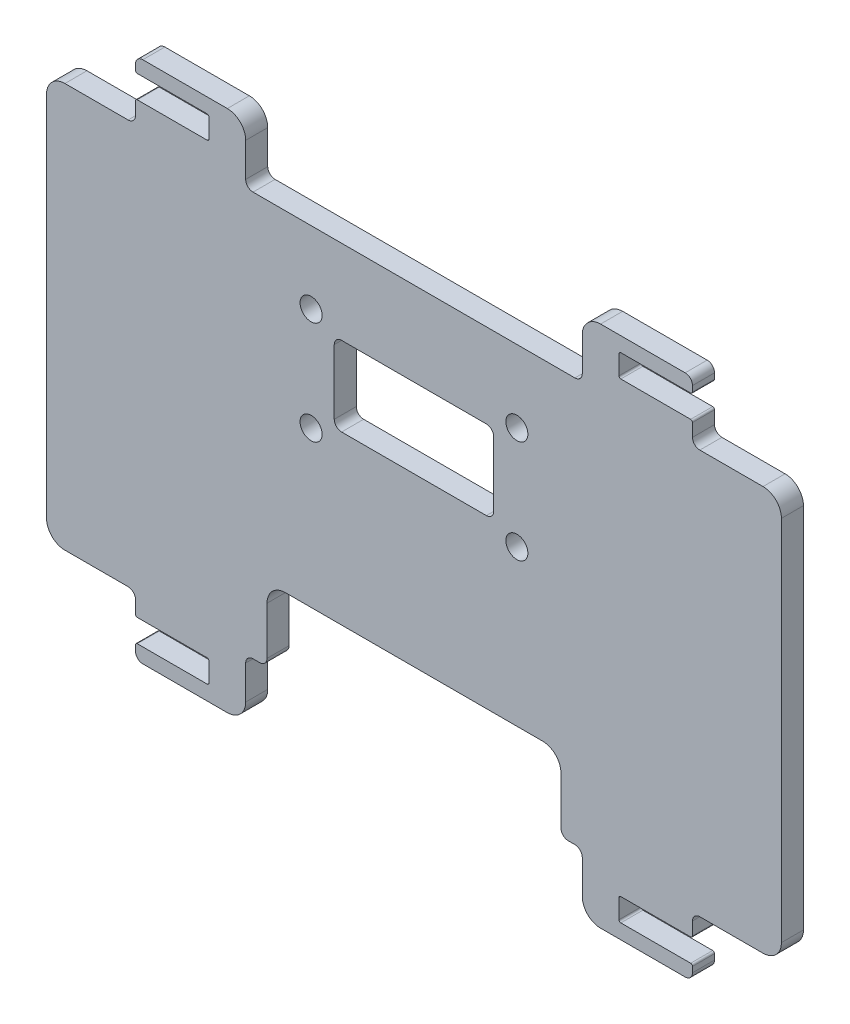
SolidWorks part; units mm, degrees
ref_plane "Alzado" through (0, 0, 0) normal (0, 0, 1) x (1, 0, 0)
ref_plane "Planta" through (0, 0, 0) normal (0, 1, 0) x (1, 0, 0)
ref_plane "Vista lateral" through (0, 0, 0) normal (1, 0, 0) x (0, 0, -1)
sketch "Croquis1" plane through (0, 0, 0) normal (0, 0, 1) x (1, 0, 0)
  line L0 (0, 16.0534) -> (0, 17.6634) construction
  line L2 (-50, 25) -> (-50, -25)
  line L4 (50, 25) -> (50, -25)
  line L5 (-50, 27.5) -> (50, -27.5) construction
  line L6 (-50, -27.5) -> (50, 27.5) construction
  line L7 (-10.85, 16.0534) -> (10.85, 16.0534)
  line L8 (-10.85, 16.0534) -> (-10.85, 5.2534)
  line L9 (-10.85, 5.2534) -> (10.85, 5.2534)
  line L10 (10.85, 16.0534) -> (10.85, 5.2534)
  line L11 (-10.85, 16.0534) -> (10.85, 5.2534) construction
  line L12 (-10.85, 5.2534) -> (10.85, 16.0534) construction
  line L13 (-14, 17.6634) -> (14, 17.6634) construction
  line L14 (0, 12.2207) -> (0, 8.6829) construction
  line L15 (-2.0239, 10.6534) -> (1.9478, 10.6534) construction
  line L16 (-37.9, -27.5) -> (-37.9, -30.5)
  line L17 (-37.9, -30.5) -> (-27.9, -30.5)
  line L18 (-27.9, -30.5) -> (-27.9, -33.6)
  line L19 (-27.9, -33.6) -> (-37.9, -33.6)
  line L20 (-37.9, -33.6) -> (-37.9, -35.6)
  line L21 (-37.9, -35.6) -> (-25.4, -35.6)
  line L22 (-22.9, -33.1) -> (-22.9, -27.5)
  line L23 (0, 2.3088) -> (0, -3.2784) construction
  line L24 (22.9, -33.1) -> (22.9, -27.5)
  line L25 (37.9, -35.6) -> (25.4, -35.6)
  line L26 (37.9, -33.6) -> (37.9, -35.6)
  line L27 (27.9, -33.6) -> (37.9, -33.6)
  line L28 (27.9, -30.5) -> (27.9, -33.6)
  line L29 (37.9, -30.5) -> (27.9, -30.5)
  line L30 (37.9, -27.5) -> (37.9, -30.5)
  line L31 (-47.5, -27.5) -> (-37.9, -27.5)
  line L32 (-22.9, -27.5) -> (22.9, -27.5)
  line L33 (37.9, -27.5) -> (47.5, -27.5)
  line L34 (-37.9, 27.5) -> (-37.9, 30.5)
  line L35 (-37.9, 30.5) -> (-27.9, 30.5)
  line L36 (-27.9, 30.5) -> (-27.9, 33.6)
  line L37 (-27.9, 33.6) -> (-37.9, 33.6)
  line L38 (-37.9, 33.6) -> (-37.9, 35.6)
  line L39 (-37.9, 35.6) -> (-25.4, 35.6)
  line L40 (-22.9, 33.1) -> (-22.9, 27.5)
  line L41 (22.9, 33.1) -> (22.9, 27.5)
  line L42 (37.9, 35.6) -> (25.4, 35.6)
  line L43 (37.9, 33.6) -> (37.9, 35.6)
  line L44 (27.9, 33.6) -> (37.9, 33.6)
  line L45 (27.9, 30.5) -> (27.9, 33.6)
  line L46 (37.9, 30.5) -> (27.9, 30.5)
  line L47 (37.9, 27.5) -> (37.9, 30.5)
  line L48 (-47.5, 27.5) -> (-37.9, 27.5)
  line L49 (-22.9, 27.5) -> (22.9, 27.5)
  line L50 (37.9, 27.5) -> (47.5, 27.5)
  line L51 (37.9, -27.5) -> (-37.9, -27.5) construction
  circle A0 centre (-14, 17.6634) radius 1.5
  circle A1 centre (14, 17.6634) radius 1.5
  circle A2 centre (14, 3.6434) radius 1.5
  circle A3 centre (-14, 3.6434) radius 1.5
  arc A4 (-50, -25) -> (-47.5, -27.5) centre (-47.5, -25) ccw
  arc A5 (47.5, -27.5) -> (50, -25) centre (47.5, -25) ccw
  arc A6 (-25.4, -35.6) -> (-22.9, -33.1) centre (-25.4, -33.1) ccw
  arc A7 (22.9, -33.1) -> (25.4, -35.6) centre (25.4, -33.1) ccw
  arc A8 (47.5, 27.5) -> (50, 25) centre (47.5, 25) cw
  arc A9 (22.9, 33.1) -> (25.4, 35.6) centre (25.4, 33.1) cw
  arc A10 (-25.4, 35.6) -> (-22.9, 33.1) centre (-25.4, 33.1) cw
  arc A11 (-47.5, 27.5) -> (-50, 25) centre (-47.5, 25) ccw
  point P0 (0, 0)
  point P6 (0, 10.6534)
  point P16 (0, 17.6634)
  point P26 (-37.9, -27.5)
  point P69 (-22.9, -35.6)
  point P72 (22.9, -35.6)
  point P78 (22.9, 35.6)
  point P81 (-22.9, 35.6)
  dimension "D7" = 3
  dimension "D21" = 2.5
  dimension "D1" = 100
  dimension "D2" = 55
  dimension "D3" = 21.7
  dimension "D4" = 10.8
  dimension "D5" = 1.61
  dimension "D6" = 28
  dimension "D8" = 12.1
  dimension "D9" = 15
  dimension "D10" = 10
  dimension "D11" = 10
  dimension "D12" = 3.1
  dimension "D13" = 3
  dimension "D14" = 2
  dimension "D15" = 15
  dimension "D16" = 3.1
  dimension "D17" = 3
  dimension "D18" = 2
  dimension "D19" = 10
  dimension "D20" = 10
  dimension "D22" = 8.1
extrude "Saliente-Extruir1" add sketch "Croquis1" along normal blind 3
sketch "Croquis2" plane through (0, 0, 0) normal (0, 0, 1) x (1, 0, 0)
  line L1 (-17.5, -17.5) -> (17.5, -17.5)
  line L2 (-20, -20) -> (-20, -37.5)
  line L3 (-20, -37.5) -> (20, -37.5)
  line L4 (20, -20) -> (20, -37.5)
  line L5 (-20, -17.5) -> (20, -37.5) construction
  line L6 (-20, -37.5) -> (20, -17.5) construction
  arc A0 (17.5, -17.5) -> (20, -20) centre (17.5, -20) cw
  arc A1 (-17.5, -17.5) -> (-20, -20) centre (-17.5, -20) ccw
  point P0 (0, -27.5)
  dimension "D3" = 2.5
  dimension "D1" = 40
  dimension "D2" = 20
extrude "Cortar-Extruir2" cut sketch "Croquis2" against normal mid plane 6 contours L3 L4 A0 L1 A1 L2
fillet "Redondeo1" radius 1 18 edges at (-10.85, 5.2534, 1.5) (10.85, 5.2534, 1.5) (10.85, 16.0534, 1.5) (-10.85, 16.0534, 1.5) (-37.9, -27.5, 1.5) (-22.9, -27.5, 1.5) (22.9, -27.5, 1.5) (37.9, -27.5, 1.5) (37.9, 27.5, 1.5) (22.9, 27.5, 1.5) (-22.9, 27.5, 1.5) (-37.9, 27.5, 1.5) (-37.9, 35.6, 1.5) (37.9, 35.6, 1.5) (37.9, -35.6, 1.5) (-37.9, -35.6, 1.5) (-20, -27.5, 1.5) (20, -27.5, 1.5)
fillet "Redondeo2" radius 0.25 16 edges at (37.9, 30.5, 1.5) (27.9, 30.5, 1.5) (27.9, 33.6, 1.5) (37.9, 33.6, 1.5) (-27.9, 30.5, 1.5) (-27.9, 33.6, 1.5) (-37.9, 30.5, 1.5) (-37.9, 33.6, 1.5) (27.9, -33.6, 1.5) (37.9, -33.6, 1.5) (27.9, -30.5, 1.5) (37.9, -30.5, 1.5) (-37.9, -33.6, 1.5) (-27.9, -33.6, 1.5) (-27.9, -30.5, 1.5) (-37.9, -30.5, 1.5)
